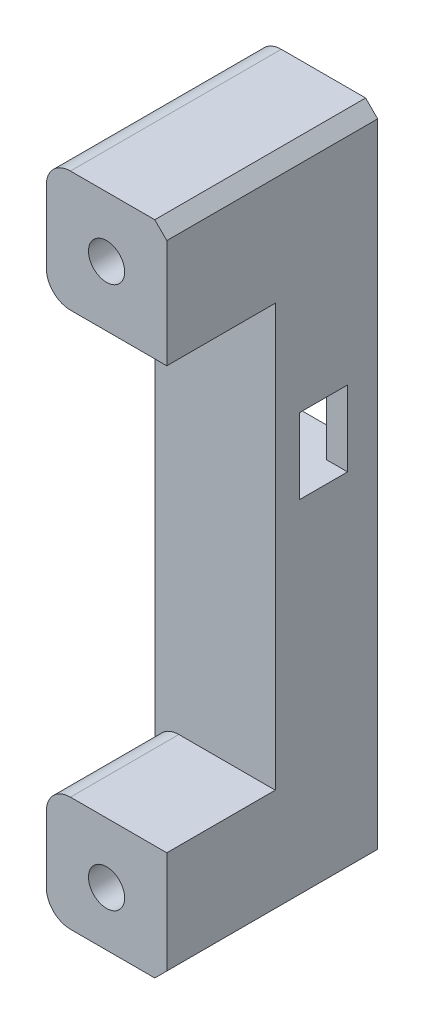
SolidWorks part; units mm, degrees
ref_plane "Спереди" through (0, 0, 0) normal (0, 0, 1) x (1, 0, 0)
ref_plane "Сверху" through (0, 0, 0) normal (0, 1, 0) x (1, 0, 0)
ref_plane "Справа" through (0, 0, 0) normal (1, 0, 0) x (0, 0, -1)
ref_plane "Плоскость4" through (0, 0, 241.9894) normal (0, 0, -1) x (-1, 0, 0)
sketch "Эскиз1" plane through (0, 0, 241.9894) normal (0, 0, -1) x (-1, 0, 0)
  line L0 (760.8505, 8.8587) -> (760.8505, -10.1413)
  line L1 (776.8505, -10.1413) -> (758.8505, -10.1413) construction
  line L2 (760.8505, -10.1413) -> (780.8505, -10.1413)
  line L3 (780.8505, -10.1413) -> (780.8505, 8.8587)
  line L4 (780.8505, 8.8587) -> (760.8505, 8.8587)
  line L5 (760.8505, 78.8587) -> (780.8505, 78.8587)
  line L6 (780.8505, 78.8587) -> (780.8505, 98.8587)
  line L7 (745.6005, 98.8587) -> (696.1005, 98.8587) construction
  line L8 (780.8505, 98.8587) -> (760.8505, 98.8587)
  line L9 (760.8505, 98.8587) -> (760.8505, 78.8587)
  circle A0 centre (770.8505, 88.8587) radius 3
  circle A1 centre (770.8505, -1.1413) radius 3
extrude "Бобышка-Вытянуть1" add sketch "Эскиз1" along normal blind 18
ref_plane "Плоскость5" through (0, 0, 223.9894) normal (0, 0, -1) x (-1, 0, 0)
sketch "Эскиз2" plane through (0, 0, 223.9894) normal (0, 0, -1) x (-1, 0, 0)
  line L0 (760.8505, 98.8587) -> (760.8505, -10.1413)
  line L1 (760.8505, -10.1413) -> (780.8505, -10.1413)
  line L2 (780.8505, -10.1413) -> (780.8505, 98.8587)
  line L3 (745.6005, 98.8587) -> (696.1005, 98.8587) construction
  line L4 (780.8505, 98.8587) -> (760.8505, 98.8587) construction
  line L5 (780.8505, 98.8587) -> (760.8505, 98.8587)
  circle A0 centre (770.8505, 88.8587) radius 3
  circle A1 centre (770.8505, -1.1413) radius 3
extrude "Бобышка-Вытянуть2" add sketch "Эскиз2" along normal blind 4
ref_plane "Плоскость6" through (0, 0, 219.9894) normal (0, 0, -1) x (-1, 0, 0)
sketch "Эскиз3" plane through (0, 0, 219.9894) normal (0, 0, -1) x (-1, 0, 0)
  line L0 (780.8505, 59.8587) -> (780.8505, 51.8587)
  line L3 (777.8505, 48.6087) -> (777.8505, 51.8587)
  line L4 (777.8505, 51.8587) -> (780.8505, 51.8587)
  line L5 (780.8505, -10.1413) -> (780.8505, 98.8587) construction
  line L6 (777.8505, 61.1087) -> (777.8505, 59.8587)
  line L7 (777.8505, 61.1087) -> (769.8505, 61.1087)
  line L8 (777.8505, 59.8587) -> (780.8505, 59.8587)
  line L10 (769.8505, 48.6087) -> (777.8505, 48.6087)
  line L11 (769.8505, 61.1087) -> (769.8505, 48.6087)
extrude "Бобышка-Вытянуть3" add sketch "Эскиз3" along normal blind 6
sketch "Эскиз4" plane through (0, 0, 219.9894) normal (0, 0, -1) x (-1, 0, 0)
  circle A0 centre (775.8505, 50.8587) radius 0.9
  circle A1 centre (775.8505, 58.8587) radius 0.9
extrude "Вырез-Вытянуть1" cut sketch "Эскиз4" along normal through all
sketch "Эскиз5" plane through (0, 0, 219.9894) normal (0, 0, -1) x (-1, 0, 0)
  line L0 (760.8505, -10.1413) -> (780.8505, -10.1413)
  line L1 (780.8505, -10.1413) -> (780.8505, 51.8587)
  line L2 (780.8505, 51.8587) -> (777.8505, 51.8587)
  line L3 (777.8505, 51.8587) -> (777.8505, 48.6087)
  line L8 (777.8505, 61.1087) -> (777.8505, 59.8587)
  line L9 (777.8505, 59.8587) -> (780.8505, 59.8587)
  line L10 (780.8505, 59.8587) -> (777.8505, 59.8587) construction
  line L11 (780.8505, 59.8587) -> (780.8505, 98.8587)
  line L12 (780.8505, 98.8587) -> (760.8505, 98.8587)
  line L13 (760.8505, 98.8587) -> (760.8505, -10.1413) construction
  line L14 (780.8505, 98.8587) -> (760.8505, 98.8587) construction
  line L16 (777.8505, 61.1087) -> (760.8505, 61.1087)
  line L17 (760.8505, 61.1087) -> (760.8505, 98.8587)
  line L18 (777.8505, 48.6087) -> (760.8505, 48.6087)
  line L19 (760.8505, 48.8587) -> (760.8505, 78.8587) construction
  line L20 (760.8505, 48.6087) -> (760.8505, -10.1413)
  circle A0 centre (770.8505, 88.8587) radius 3
  circle A1 centre (770.8505, -1.1413) radius 3
extrude "Бобышка-Вытянуть4" add sketch "Эскиз5" along normal blind 13
chamfer "Фаска1" distance 2 angle 45 3 edges at (-780.8505, 51.8587, 210.4894) (-780.8505, 55.8587, 213.9894) (-780.8505, 59.8587, 210.4894)
ref_plane "Плоскость7" through (0, 0, 206.9894) normal (0, 0, -1) x (-1, 0, 0)
sketch "Эскиз6" plane through (0, 0, 206.9894) normal (0, 0, -1) x (-1, 0, 0)
  line L0 (760.8505, 61.1087) -> (764.3505, 61.1087)
  line L1 (760.8505, 61.1087) -> (777.8505, 61.1087) construction
  line L2 (764.3505, 61.1087) -> (764.3505, 48.6087)
  line L3 (777.8505, 48.6087) -> (760.8505, 48.6087) construction
  line L4 (764.3505, 48.6087) -> (760.8505, 48.6087)
  line L5 (760.8505, 48.8587) -> (760.8505, 9.8587) construction
  line L6 (760.8505, 48.6087) -> (760.8505, -10.1413) construction
  line L7 (760.8505, 48.6087) -> (760.8505, 61.1087)
extrude "Бобышка-Вытянуть5" add sketch "Эскиз6" against normal blind 5
fillet "Скругление1" radius 4 4 edges at (-780.8505, -10.1413, 224.4894) (-780.8505, 8.8587, 232.9894) (-780.8505, 78.8587, 232.9894) (-780.8505, 98.8587, 224.4894)
chamfer "Фаска2" distance 2 angle 45 2 edges at (-760.8505, -10.1413, 224.4894) (-760.8505, 98.8587, 224.4894)
